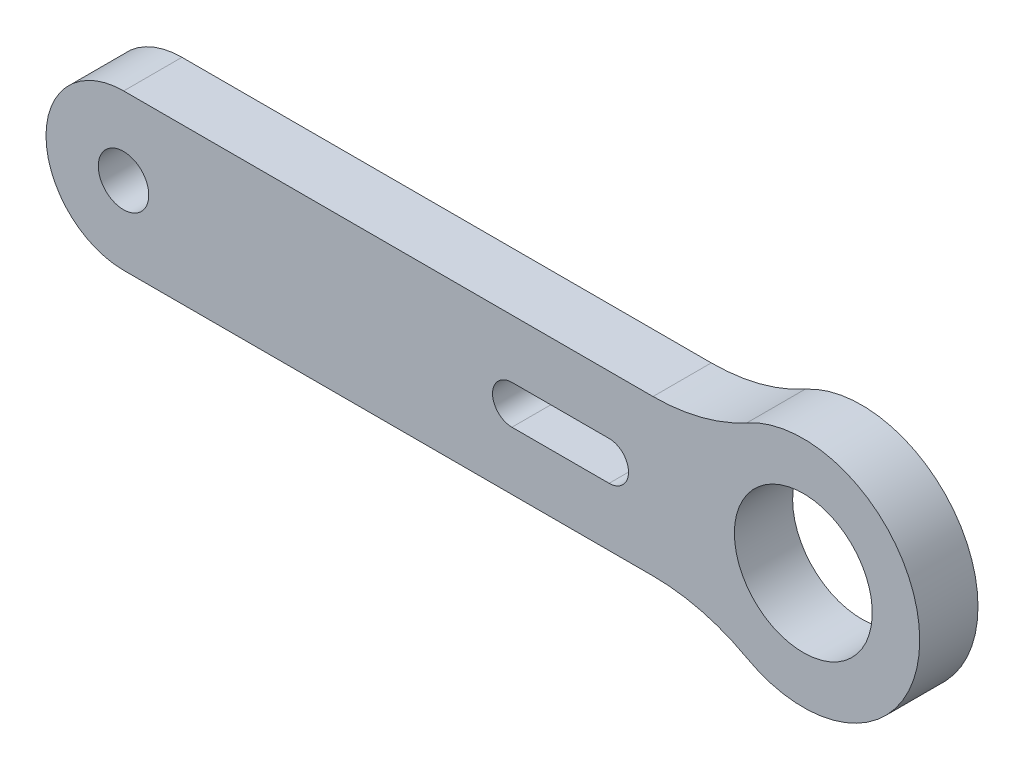
SolidWorks part; units mm, degrees
ref_plane "前视基准面" through (0, 0, 0) normal (0, 0, 1) x (1, 0, 0)
ref_plane "上视基准面" through (0, 0, 0) normal (0, 1, 0) x (1, 0, 0)
ref_plane "右视基准面" through (0, 0, 0) normal (1, 0, 0) x (0, 0, -1)
ref_plane "基准面1" through (0, 0, 3) normal (0, 0, 1) x (1, 0, 0)
sketch "草图1" plane through (0, 0, 3) normal (0, 0, 1) x (1, 0, 0)
  line L0 (8.3788, 5) -> (13.3804, 5)
  line L1 (13.3804, 3.0005) -> (8.3788, 3.0005)
  line L2 (-11.611, 0) -> (15.6462, 0)
  line L3 (15.6408, 8) -> (-11.611, 8)
  arc A0 (8.3788, 3.0005) -> (8.3788, 5) centre (8.3788, 4.0003) cw
  arc A1 (13.3804, 5) -> (13.3804, 3.0005) centre (13.3804, 4.0003) cw
  circle A2 centre (23.3793, 4.0005) radius 3.55
  arc A3 (-11.611, 8) -> (-11.611, 0) centre (-11.611, 4) ccw
  arc A4 (15.6462, 0) -> (20.4804, -1.2461) centre (15.6462, -10) cw
  arc A5 (20.4804, -1.2461) -> (20.4784, 9.248) centre (23.3783, 4.0015) ccw
  arc A6 (20.4784, 9.248) -> (15.6408, 8) centre (15.6408, 18) cw
  circle A7 centre (-11.6194, 4.0002) radius 1.3
extrude "凸台-拉伸1" add sketch "草图1" against normal blind 3
